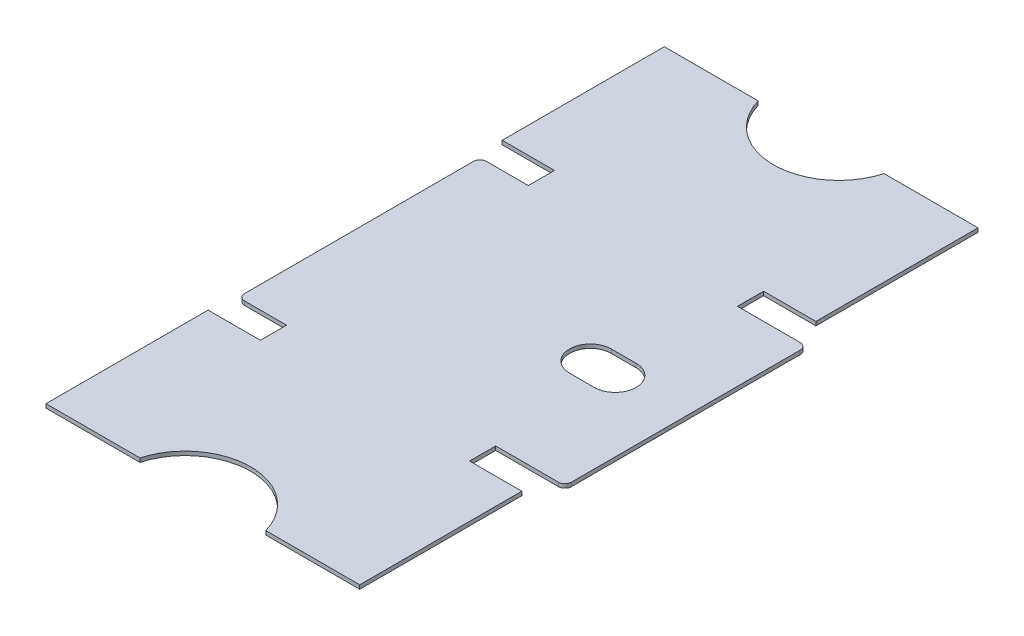
SolidWorks part; units mm, degrees
material "Медь"
ref_plane "Спереди" through (0, 0, 0) normal (0, 0, 1) x (1, 0, 0)
ref_plane "Сверху" through (0, 0, 0) normal (0, 1, 0) x (1, 0, 0)
ref_plane "Справа" through (0, 0, 0) normal (1, 0, 0) x (0, 0, -1)
sketch "Эскиз1" plane through (0, 0, 0) normal (0, 1, 0) x (1, 0, 0)
  line L0 (-17.4045, 6.7002) -> (-15.5045, 6.7002)
  line L1 (-17.4045, 3.5002) -> (-15.5045, 3.5002)
  line L2 (-11.4045, 16.3502) -> (-11.4045, 28.7502)
  line L3 (-11.4045, 28.7502) -> (-18.5902, 28.7502)
  line L4 (-28.2188, 28.7502) -> (-35.4045, 28.7502)
  line L5 (-35.4045, 28.7502) -> (-35.4045, 16.3502)
  line L6 (-35.4045, 16.3502) -> (-31.4045, 16.3502)
  line L7 (-31.4045, 16.3502) -> (-31.4045, 14.3502)
  line L8 (-31.4045, 14.3502) -> (-34.6045, 14.3502)
  line L9 (-35.1045, 13.8502) -> (-35.1045, -3.6498)
  line L10 (-34.6045, -4.1498) -> (-31.4045, -4.1498)
  line L11 (-31.4045, -4.1498) -> (-31.4045, -6.1498)
  line L12 (-31.4045, -6.1498) -> (-35.4045, -6.1498)
  line L13 (-35.4045, -6.1498) -> (-35.4045, -18.5498)
  line L14 (-35.4045, -18.5498) -> (-28.2188, -18.5498)
  line L15 (-18.5902, -18.5498) -> (-11.4045, -18.5498)
  line L16 (-11.4045, -18.5498) -> (-11.4045, -6.1498)
  line L17 (-11.4045, -6.1498) -> (-15.4045, -6.1498)
  line L18 (-15.4045, -6.1498) -> (-15.4045, -4.1498)
  line L19 (-15.4045, -4.1498) -> (-10.6045, -4.1498)
  line L20 (-10.1045, -3.6498) -> (-10.1045, 13.8502)
  line L21 (-10.6045, 14.3502) -> (-15.4045, 14.3502)
  line L22 (-15.4045, 14.3502) -> (-15.4045, 16.3502)
  line L23 (-15.4045, 16.3502) -> (-11.4045, 16.3502)
  arc A0 (-15.5045, 3.5002) -> (-15.5045, 6.7002) centre (-15.5045, 5.1002) ccw
  arc A1 (-17.4045, 6.7002) -> (-17.4045, 3.5002) centre (-17.4045, 5.1002) ccw
  arc A2 (-28.2188, 28.7502) -> (-18.5902, 28.7502) centre (-23.4045, 30.1002) ccw
  arc A3 (-34.6045, 14.3502) -> (-35.1045, 13.8502) centre (-34.6045, 13.8502) ccw
  arc A4 (-35.1045, -3.6498) -> (-34.6045, -4.1498) centre (-34.6045, -3.6498) ccw
  arc A5 (-18.5902, -18.5498) -> (-28.2188, -18.5498) centre (-23.4045, -19.8998) ccw
  arc A6 (-10.6045, -4.1498) -> (-10.1045, -3.6498) centre (-10.6045, -3.6498) ccw
  arc A7 (-10.1045, 13.8502) -> (-10.6045, 14.3502) centre (-10.6045, 13.8502) ccw
extrude "Бобышка-Вытянуть1" add sketch "Эскиз1" along normal blind 0.3
